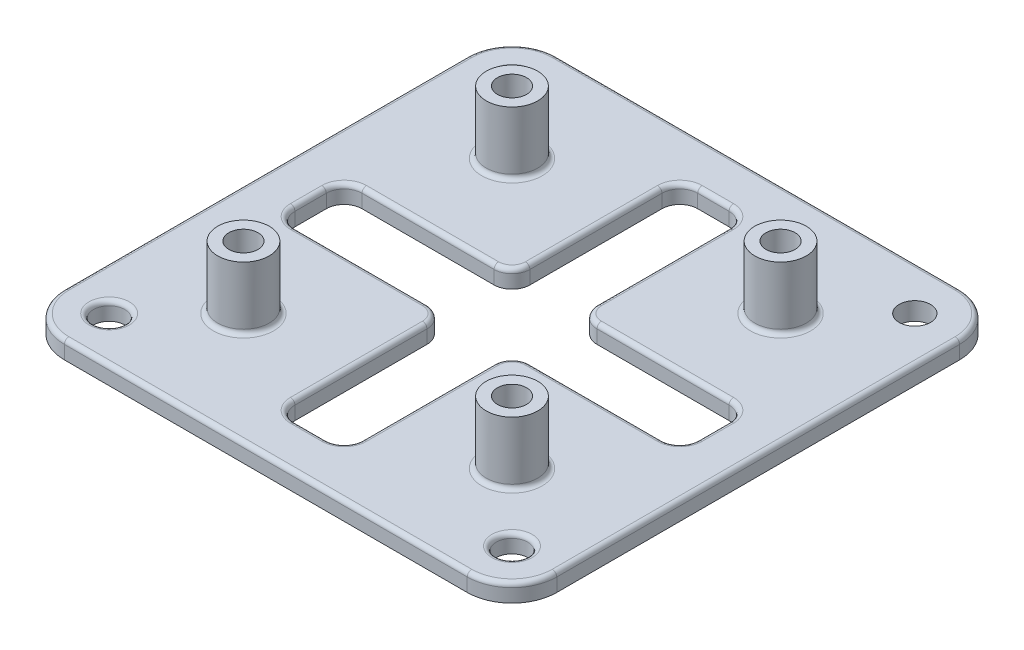
SolidWorks part; units mm, degrees
ref_plane "Front" through (0, 0, 0) normal (0, 0, 1) x (1, 0, 0)
ref_plane "Top" through (0, 0, 0) normal (0, 1, 0) x (1, 0, 0)
ref_plane "Right" through (0, 0, 0) normal (1, 0, 0) x (0, 0, -1)
sketch "Sketch1" plane through (0, 0, 0) normal (0, 1, 0) x (1, 0, 0)
  line L0 (-3.75, -3.75) -> (-3.75, -22.5)
  line L1 (-22.5, 27.5) -> (22.5, 27.5)
  line L2 (-27.5, 22.5) -> (-27.5, -22.5)
  line L3 (-22.5, -27.5) -> (22.5, -27.5)
  line L4 (27.5, 22.5) -> (27.5, -22.5)
  line L5 (-27.5, 27.5) -> (27.5, -27.5) construction
  line L6 (-27.5, -27.5) -> (27.5, 27.5) construction
  line L7 (-3.75, 22.5) -> (3.75, 22.5)
  line L8 (-3.75, 22.5) -> (-3.75, 3.75)
  line L9 (-3.75, -22.5) -> (3.75, -22.5)
  line L10 (3.75, 22.5) -> (3.75, 3.75)
  line L11 (-3.75, 22.5) -> (3.75, -22.5) construction
  line L12 (-3.75, -22.5) -> (3.75, 22.5) construction
  line L13 (-22.5, 3.75) -> (-3.75, 3.75)
  line L14 (-22.5, 3.75) -> (-22.5, -3.75)
  line L15 (-22.5, -3.75) -> (-3.75, -3.75)
  line L16 (22.5, 3.75) -> (22.5, -3.75)
  line L17 (-22.5, 3.75) -> (22.5, -3.75) construction
  line L18 (-22.5, -3.75) -> (22.5, 3.75) construction
  line L19 (3.75, -3.75) -> (22.5, -3.75)
  line L20 (3.75, -3.75) -> (3.75, -22.5)
  line L21 (3.75, 3.75) -> (22.5, 3.75)
  circle A0 centre (-22.5, 22.5) radius 1.75
  circle A1 centre (22.5, 22.5) radius 1.75
  circle A2 centre (22.5, -22.5) radius 1.75
  circle A3 centre (-22.5, -22.5) radius 1.75
  arc A4 (27.5, -22.5) -> (22.5, -27.5) centre (22.5, -22.5) cw
  arc A5 (27.5, 22.5) -> (22.5, 27.5) centre (22.5, 22.5) ccw
  arc A6 (-22.5, 27.5) -> (-27.5, 22.5) centre (-22.5, 22.5) ccw
  arc A7 (-22.5, -27.5) -> (-27.5, -22.5) centre (-22.5, -22.5) cw
  point P0 (0, 0)
  point P16 (0, 0)
  point P31 (0, 0)
  dimension "D8" = 3.5
  dimension "D9" = 3.5
  dimension "D10" = 3.5
  dimension "D11" = 3.5
  dimension "D13" = 5
  dimension "D1" = 55
  dimension "D2" = 55
  dimension "D3" = 45
  dimension "D4" = 45
  dimension "D5" = 5
  dimension "D6" = 5
  dimension "D7" = 5
  dimension "D12" = 45
  dimension "D16" = 7.5
extrude "Boss-Extrude1" add sketch "Sketch1" along normal blind 2
sketch "Sketch2" plane through (0, 2, 0) normal (0, 1, 0) x (1, 0, 0)
  line L0 (-15, 15) -> (15, 15) construction
  line L1 (22.5, 27.5) -> (-22.5, 27.5) construction
  line L2 (15, -15) -> (15, 15) construction
  line L3 (27.5, -22.5) -> (27.5, 22.5) construction
  circle A0 centre (-15, 15) radius 1.625
  circle A1 centre (15, 15) radius 1.625
  circle A2 centre (15, -15) radius 1.625
  circle A3 centre (-15, -15) radius 1.625
  circle A4 centre (-15, 15) radius 2.875
  circle A5 centre (15, 15) radius 2.875
  circle A6 centre (15, -15) radius 2.875
  circle A7 centre (-15, -15) radius 2.875
  point P8 (0, 15)
  point P11 (0, 27.5)
  point P14 (27.5, 0)
  point P15 (15, 0)
  point P16 (0, 0)
  point P17 (0, 0)
  dimension "D1" = 3.25
  dimension "D4" = 1.25
  dimension "D2" = 30
  dimension "D3" = 30
extrude "Boss-Extrude2" add sketch "Sketch2" along normal blind 7
fillet "Fillet3" radius 2 12 edges at (-3.75, 1, -22.5) (3.75, 1, -22.5) (-3.75, 1, -3.75) (3.75, 1, -3.75) (22.5, 1, -3.75) (22.5, 1, 3.75) (3.75, 1, 3.75) (3.75, 1, 22.5) (-3.75, 1, 22.5) (-3.75, 1, 3.75) (-22.5, 1, 3.75) (-22.5, 1, -3.75)
sketch "Sketch3" plane through (0, 2, 0) normal (0, 1, 0) x (1, 0, 0)
  circle A0 centre (-15, 15) radius 1.625
  circle A1 centre (15, 15) radius 1.625
  circle A2 centre (15, -15) radius 1.625
  circle A3 centre (-15, -15) radius 1.625
extrude "Cut-Extrude1" cut sketch "Sketch3" against normal blind 7
fillet "Fillet4" radius 0.5 39 edges at (-26.0355, 2, 26.0355) (-27.5, 2, 0) (-26.0355, 2, -26.0355) (0, 2, -27.5) (26.0355, 2, -26.0355) (27.5, 2, 0) (26.0355, 2, 26.0355) (-4.3358, 2, -4.3358) (-3.75, 2, -13.125) (-3.1642, 2, -21.9142) (0, 2, -22.5) (3.1642, 2, -21.9142) (3.75, 2, -13.125) (4.3358, 2, -4.3358) (13.125, 2, -3.75) (21.9142, 2, -3.1642) (22.5, 2, 0) (21.9142, 2, 3.1642) (13.125, 2, 3.75) (4.3358, 2, 4.3358) (3.75, 2, 13.125) (3.1642, 2, 21.9142) (0, 2, 22.5) (-3.1642, 2, 21.9142) (-3.75, 2, 13.125) (-4.3358, 2, 4.3358) (-13.125, 2, 3.75) (-21.9142, 2, 3.1642) (-22.5, 2, 0) (-21.9142, 2, -3.1642) (0, 2, 27.5) (22.5, 2, 24.25) (-22.5, 2, -20.75) (-22.5, 2, 24.25) (-13.125, 2, -3.75) (15, 2, -17.875) (15, 2, 12.125) (-15, 2, 12.125) (-15, 2, -17.875)
